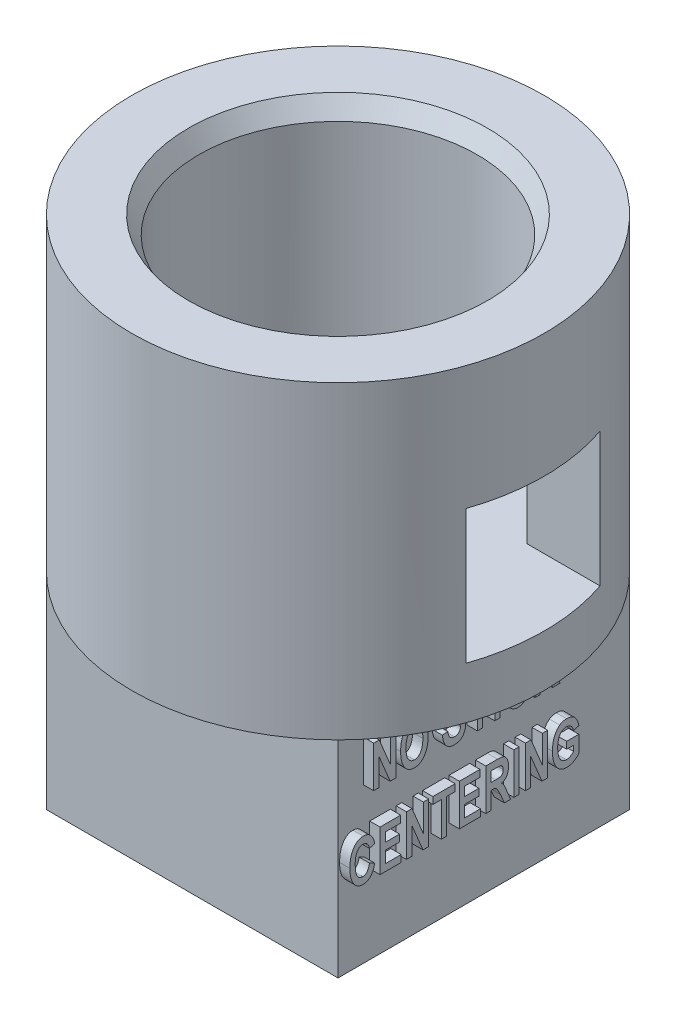
SolidWorks part; units mm, degrees
ref_plane "Спереди" through (0, 0, 0) normal (0, 0, 1) x (1, 0, 0)
ref_plane "Сверху" through (0, 0, 0) normal (0, 1, 0) x (1, 0, 0)
ref_plane "Справа" through (0, 0, 0) normal (1, 0, 0) x (0, 0, -1)
sketch "Sketch1" plane through (0, 0, 0) normal (0, 1, 0) x (1, 0, 0)
  line L1 (4.8, -4.8) -> (-4.8, -4.8)
  line L2 (4.8, -4.8) -> (4.8, 4.8)
  line L3 (4.8, 4.8) -> (-4.8, 4.8)
  line L4 (-4.8, -4.8) -> (-4.8, 4.8)
  line L5 (4.8, -4.8) -> (-4.8, 4.8) construction
  line L6 (4.8, 4.8) -> (-4.8, -4.8) construction
  point P0 (0, 0)
  dimension "D1" = 9.6
extrude "Boss-Extrude1" add sketch "Sketch1" along normal blind 28
sketch "Sketch2" plane through (0, 28, 0) normal (0, 1, 0) x (1, 0, 0)
  circle A0 centre (0, 0) radius 20
  dimension "D1" = 40
extrude "Boss-Extrude2" add sketch "Sketch2" along normal blind 30
sketch "Sketch3" plane through (0, 58, 0) normal (0, 1, 0) x (1, 0, 0)
  circle A0 centre (0, 0) radius 13.5
  dimension "D1" = 27
extrude "Cut-Extrude1" cut sketch "Sketch3" against normal blind 25
chamfer "Chamfer1" distance 1 angle 60 4 edges at (4.8, 0, 0) (0, 0, -4.8) (-4.8, 0, 0) (0, 0, 4.8)
chamfer "Chamfer2" distance 1 angle 60 1 edges at (0, 58, 13.5)
sketch "Sketch4" plane through (0, 28, 0) normal (0, -1, 0) x (1, 0, 0)
  line L1 (-14.1421, 14.1421) -> (14.1421, 14.1421)
  line L2 (-14.1421, 14.1421) -> (-14.1421, -14.1421)
  line L3 (-14.1421, -14.1421) -> (14.1421, -14.1421)
  line L4 (14.1421, 14.1421) -> (14.1421, -14.1421)
  line L5 (-14.1421, 14.1421) -> (14.1421, -14.1421) construction
  line L6 (-14.1421, -14.1421) -> (14.1421, 14.1421) construction
  line L7 (-7.75, 7.75) -> (7.75, 7.75)
  line L8 (-7.75, 7.75) -> (-7.75, -7.75)
  line L9 (-7.75, -7.75) -> (7.75, -7.75)
  line L10 (7.75, 7.75) -> (7.75, -7.75)
  line L11 (-7.75, 7.75) -> (7.75, -7.75) construction
  line L12 (-7.75, -7.75) -> (7.75, 7.75) construction
  circle A0 centre (0, 0) radius 20 construction
  point P0 (0, 0)
  point P9 (0, 0)
  dimension "D1" = 15.5
extrude "Boss-Extrude3" add sketch "Sketch4" along normal blind 20
sketch "Sketch6" plane through (-14.1421, 0, 0) normal (-1, 0, 0) x (0, 0, 1)
  line L0 (-14.1421, 23) -> (14.1421, 23) construction
  line L1 (-14.1421, 8) -> (-14.1421, 28) construction
  line L2 (14.1421, 8) -> (14.1421, 28) construction
  line L3 (14.1421, 28) -> (-14.1421, 28) construction
  text T0 "REMOVE\r\n  AFTER\r\n  FLIGHT" font "Arial" height 4
  dimension "D1" = 5
extrude "Boss-Extrude4" add sketch "Sketch6" along normal blind 1
sketch "Sketch7" plane through (14.1421, 0, 0) normal (1, 0, 0) x (0, 0, -1)
  line L0 (-14.1421, 23) -> (14.1421, 23) construction
  line L1 (-14.1421, 8) -> (-14.1421, 28) construction
  line L2 (14.1421, 8) -> (14.1421, 28) construction
  line L3 (14.1421, 28) -> (-14.1421, 28) construction
  text T0 "<b>  NO STICK</b>\r\n<b>CENTERING</b>" font "Arial" height 4
  dimension "D1" = 5
extrude "Boss-Extrude5" add sketch "Sketch7" along normal blind 1
sketch "Sketch8" plane through (0, 33, 0) normal (0, 1, 0) x (1, 0, 0)
  line L0 (13.5, 0) -> (-13.5, 0) construction
  line L2 (7, -6.5) -> (20, -6.5)
  line L3 (7, -6.5) -> (7, 6.5)
  line L4 (7, 6.5) -> (20, 6.5)
  line L5 (20, -6.5) -> (20, 6.5)
  line L6 (7, -6.5) -> (20, 6.5) construction
  line L7 (7, 6.5) -> (20, -6.5) construction
  circle A2 centre (0, 0) radius 13.5 construction
  point P9 (13.5, 0)
  dimension "D1" = 13
extrude "Cut-Extrude2" cut sketch "Sketch8" along normal blind 13
chamfer "Chamfer3" distance 4 angle 50 1 edges at (13.5, 46, 0)
